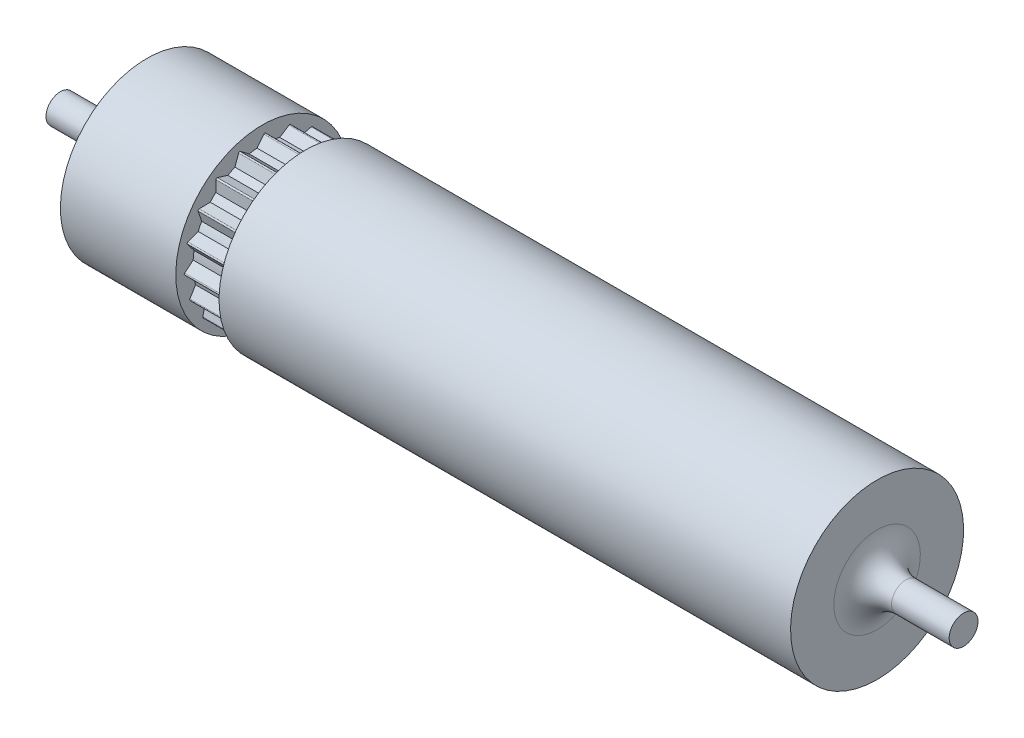
SolidWorks part; units mm, degrees
ref_plane "Plan de face" through (0, 0, 0) normal (0, 0, 1) x (1, 0, 0)
ref_plane "Plan de dessus" through (0, 0, 0) normal (0, 1, 0) x (1, 0, 0)
ref_plane "Plan de droite" through (0, 0, 0) normal (1, 0, 0) x (0, 0, -1)
sketch "Esquisse1" plane through (0, 0, 0) normal (0, 0, 1) x (1, 0, 0)
  line L0 (-81.1413, 0) -> (75.2437, 0) construction
  line L1 (-78.3, 0) -> (-78.3, 2.5)
  line L2 (-78.3, 2.5) -> (-63.3, 2.5)
  line L3 (-63.3, 2.5) -> (-63.3, 15)
  line L4 (-63.3, 15) -> (-43.3, 15)
  line L5 (-78.3, 0) -> (78.3, 0)
  line L6 (0, 15) -> (0, 0) construction
  line L7 (63.3, 2.5) -> (63.3, 15)
  line L8 (78.3, 2.5) -> (63.3, 2.5)
  line L9 (78.3, 0) -> (78.3, 2.5)
  line L10 (-35.8, 15) -> (63.3, 15)
  line L12 (-43.3, 15) -> (-43.3, 12)
  line L13 (-43.3, 12) -> (-35.8, 12)
  line L14 (-35.8, 15) -> (-35.8, 12)
  dimension "D1" = 78.3
  dimension "D2" = 15
  dimension "D3" = 2.5
  dimension "D4" = 15
  dimension "D5" = 20
  dimension "D6" = 7.5
  dimension "D7" = 3
revolve "Révolution1" add sketch "Esquisse1" angle 360 about L5
fillet "Congé1" radius 5 2 edges at (63.3, -2.5, 0) (-63.3, -2.5, 0)
sketch "Esquisse3" plane through (-43.3, 0, 0) normal (1, 0, 0) x (0, 0, -1)
  line L0 (0, 0) -> (0.4912, 14.992) construction
  line L1 (-1.5159, 11.3463) -> (2.4996, 11.2147) construction
  line L2 (0.6017, 13.4516) -> (2.1344, 11.2267)
  line L3 (0.2801, 13.4622) -> (-1.3949, 11.3423)
  line L4 (-1.3949, 11.3423) -> (2.1344, 11.2267)
  circle A0 centre (0, 0) radius 15 construction
  arc A1 (0.2801, 13.4622) -> (0.6017, 13.4516) centre (0.437, 13.3382) cw
  point P12 (0.4481, 13.6747)
  dimension "D1" = 0.2
extrude "Boss.-Extru.1" add sketch "Esquisse3" along normal up to surface (7.5 mm away) up to face at (-35.8, -12, 0)
pattern_circular "Répétition circulaire1" count 19 over 360 about axis through (0, 0, 0) along (1, 0, 0) of "Boss.-Extru.1"
